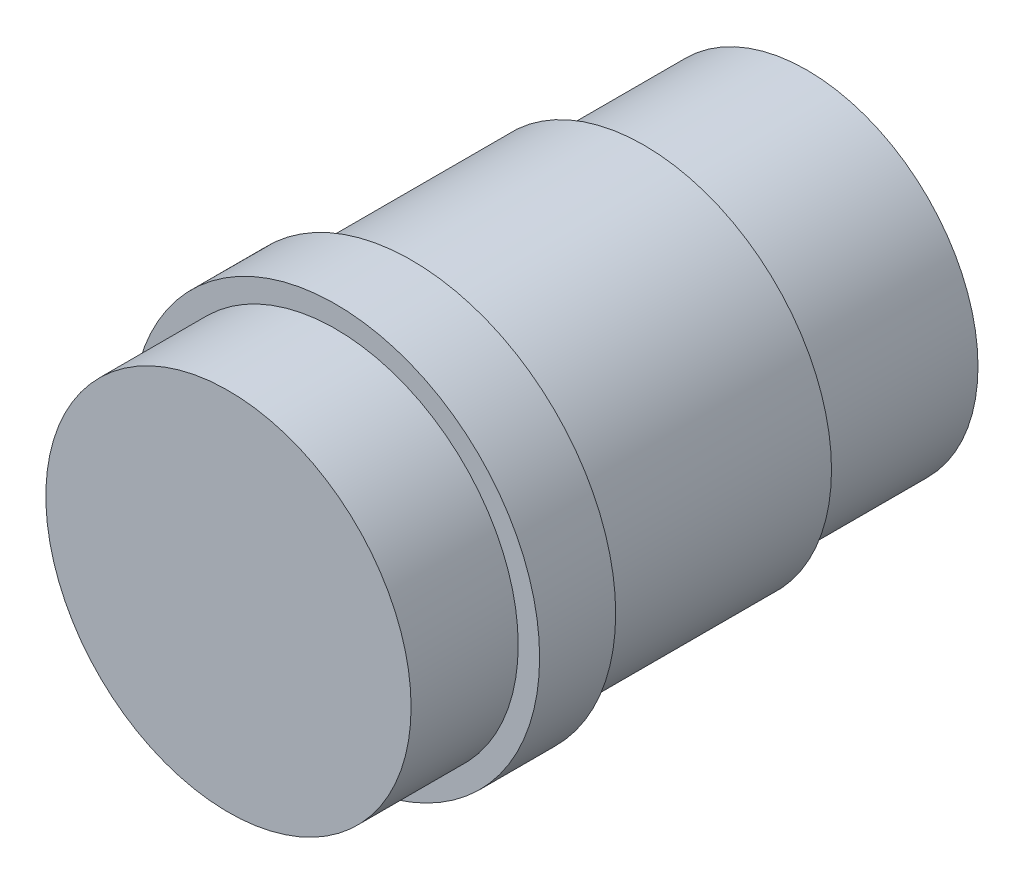
SolidWorks part; units mm, degrees
ref_plane "Alzado" through (0, 0, 0) normal (0, 0, 1) x (1, 0, 0)
ref_plane "Planta" through (0, 0, 0) normal (0, 1, 0) x (1, 0, 0)
ref_plane "Vista lateral" through (0, 0, 0) normal (1, 0, 0) x (0, 0, -1)
sketch "Croquis1" plane through (0, 0, 0) normal (1, 0, 0) x (0, 0, -1)
  line L0 (0, 0) -> (27, 0)
  line L1 (0, 8.525) -> (5, 8.525)
  line L2 (0, 8.525) -> (0, 0)
  line L3 (5, 9.525) -> (8.55, 9.525)
  line L4 (5, 9.525) -> (5, 8.525)
  line L5 (8.55, 8.75) -> (19.4, 8.75)
  line L6 (8.55, 9.525) -> (8.55, 8.75)
  line L7 (19.4, 7.9883) -> (27, 7.9883)
  line L8 (27, 7.9883) -> (27, 0)
  line L9 (19.4, 8.75) -> (19.4, 7.9883)
  dimension "D1" = 27
  dimension "D2" = 8.525
  dimension "D3" = 9.525
  dimension "D4" = 5
  dimension "D5" = 3.55
  dimension "D6" = 8.75
  dimension "D7" = 19.4
  dimension "D8" = 7.9883
revolve "Revolución1" add sketch "Croquis1" angle 360 about L0
